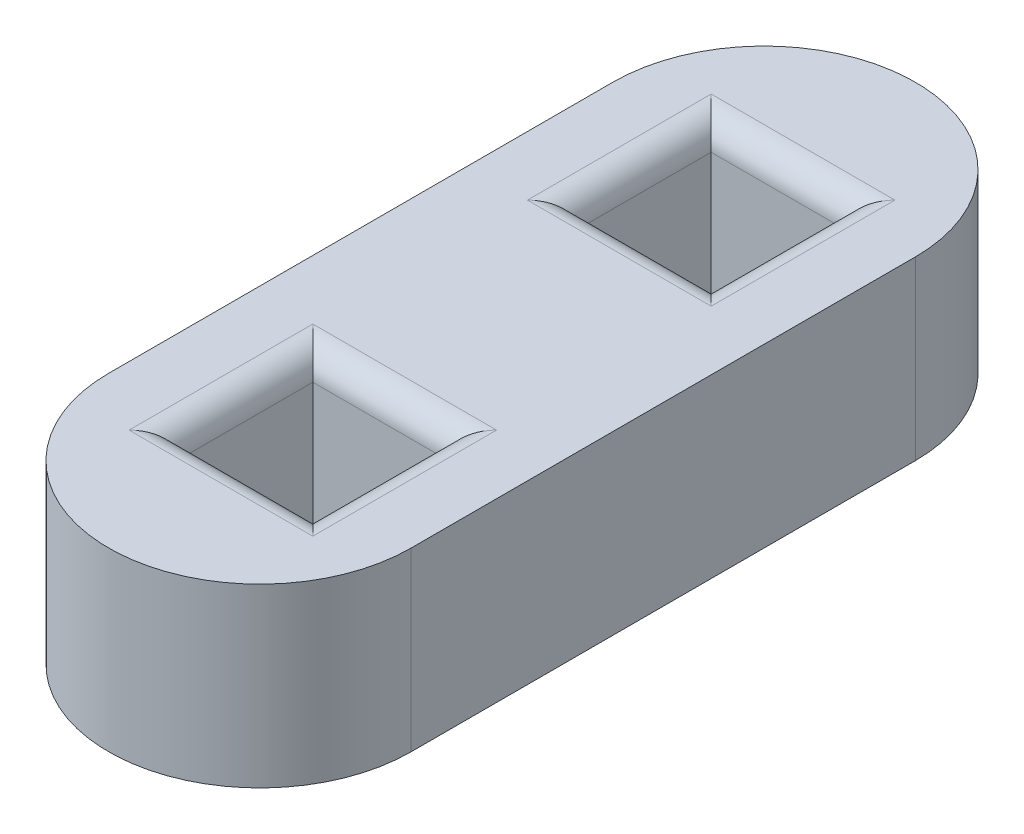
SolidWorks part; units mm, degrees
ref_plane "Front Plane" through (0, 0, 0) normal (0, 0, 1) x (1, 0, 0)
ref_plane "Top Plane" through (0, 0, 0) normal (0, 1, 0) x (1, 0, 0)
ref_plane "Right Plane" through (0, 0, 0) normal (1, 0, 0) x (0, 0, -1)
sketch "Sketch4" plane through (0, 0, 0) normal (0, 1, 0) x (1, 0, 0)
  line L0 (0, 0) -> (0, -20) construction
  line L1 (6, 0) -> (6, -20)
  line L2 (-6, 0) -> (-6, -20)
  line L3 (6.5101, -10) -> (-5.9754, -10) construction
  line L4 (-2.644, -15.256) -> (2.644, -15.256)
  line L5 (-2.644, -4.744) -> (2.644, -4.744)
  line L6 (-2.644, -4.744) -> (-2.644, 0.544)
  line L7 (-2.644, 0.544) -> (2.644, 0.544)
  line L8 (2.644, -4.744) -> (2.644, 0.544)
  line L9 (-2.644, -4.744) -> (2.644, 0.544) construction
  line L10 (-2.644, 0.544) -> (2.644, -4.744) construction
  line L11 (2.644, -15.256) -> (2.644, -20.544)
  line L12 (-2.644, -20.544) -> (2.644, -20.544)
  line L13 (-2.644, -15.256) -> (-2.644, -20.544)
  arc A0 (6, 0) -> (-6, 0) centre (0, 0) ccw
  arc A1 (-6, -20) -> (6, -20) centre (0, -20) ccw
  point P3 (0, -10)
  point P10 (0, -2.1)
  dimension "D2" = 6
  dimension "D1" = 20
  dimension "D3" = 5.288
  dimension "D4" = 7.9
  dimension "D5" = 5.288
extrude "Boss-Extrude1" add sketch "Sketch4" along normal blind 7
fillet "Fillet1" radius 1 16 edges at (-2.644, 7, 17.9) (0, 7, 20.544) (2.644, 7, 17.9) (0, 7, 15.256) (2.644, 0, 17.9) (0, 0, 20.544) (-2.644, 0, 17.9) (0, 0, 15.256) (0, 0, 4.744) (2.644, 0, 2.1) (0, 0, -0.544) (-2.644, 0, 2.1) (0, 7, 4.744) (2.644, 7, 2.1) (-2.644, 7, 2.1) (0, 7, -0.544)
